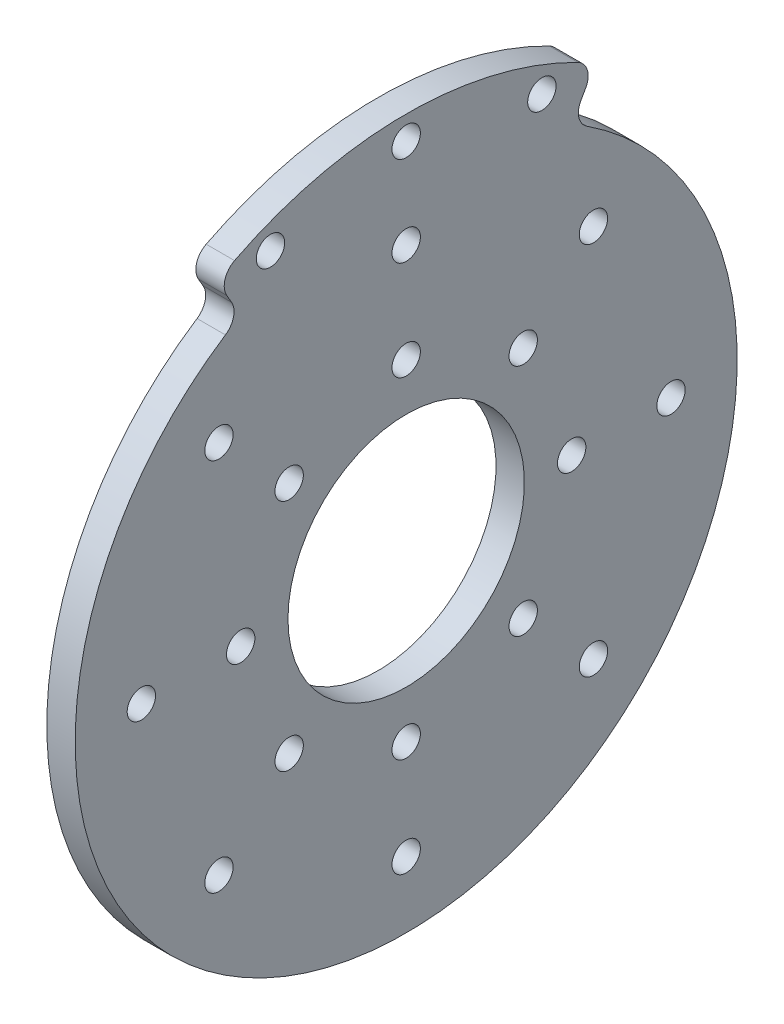
SolidWorks part; units mm, degrees
ref_plane "前视基准面" through (0, 0, 0) normal (0, 0, 1) x (1, 0, 0)
ref_plane "上视基准面" through (0, 0, 0) normal (0, 1, 0) x (1, 0, 0)
ref_plane "右视基准面" through (0, 0, 0) normal (1, 0, 0) x (0, 0, -1)
other "Configuration Table"
sketch "草图1" plane through (0, 0, 0) normal (1, 0, 0) x (0, 0, -1)
  circle A0 centre (0, 0) radius 35
  dimension "D1" = 70
extrude "凸台-拉伸1" add sketch "草图1" along normal blind 3
sketch "草图2" plane through (3, 0, 0) normal (1, 0, 0) x (0, 0, -1)
  circle A0 centre (0, 0) radius 26
  circle A1 centre (0, 0) radius 30
  circle A2 centre (0, 0) radius 28
  circle A3 centre (0, 28) radius 1.5
  circle A4 centre (19.799, 19.799) radius 1.5
  circle A5 centre (28, 0) radius 1.5
  circle A6 centre (19.799, -19.799) radius 1.5
  circle A7 centre (0, -28) radius 1.5
  circle A8 centre (-19.799, -19.799) radius 1.5
  circle A9 centre (-28, 0) radius 1.5
  circle A10 centre (-19.799, 19.799) radius 1.5
  point P24 (0, 0)
  dimension "D1" = 52
  dimension "D2" = 60
  dimension "D3" = 56
  dimension "D4" = 3
  dimension "D5" = 8
extrude "切除-拉伸1" cut sketch "草图2" against normal blind 3 contours A2 A10 | A2 A10 | A2 A6 | A2 A6 | A2 A7 | A2 A7 | A2 A8 | A2 A8 | A2 A9 | A2 A9 | A3 | A4 | A5
sketch "草图3" plane through (3, 0, 0) normal (1, 0, 0) x (0, 0, -1)
  circle A0 centre (0, 0) radius 15
  circle A1 centre (0, 0) radius 17.5
  circle A2 centre (0, 17.5) radius 1.5
  circle A3 centre (12.3744, 12.3744) radius 1.5
  circle A4 centre (17.5, 0) radius 1.5
  circle A5 centre (12.3744, -12.3744) radius 1.5
  circle A6 centre (0, -17.5) radius 1.5
  circle A7 centre (-12.3744, -12.3744) radius 1.5
  circle A8 centre (-17.5, 0) radius 1.5
  circle A9 centre (-12.3744, 12.3744) radius 1.5
  point P22 (0, 0)
  dimension "D1" = 30
  dimension "D2" = 35
  dimension "D3" = 3
  dimension "D4" = 8
extrude "切除-拉伸2" cut sketch "草图3" against normal blind 3 contours A9 | A2 | A3 | A4 | A5 | A6 | A7 | A8
sketch "草图4" plane through (0, 0, 0) normal (-1, 0, 0) x (0, 0, 1)
  circle A0 centre (0, 0) radius 12.5
  dimension "D1" = 25
extrude "切除-拉伸3" cut sketch "草图4" against normal blind 3
sketch "草图5" plane through (3, 0, 0) normal (1, 0, 0) x (0, 0, -1)
  line L0 (0, 0) -> (-20, 34.641)
  line L1 (0, 0) -> (20, 34.641)
  line L2 (-20, 34.641) -> (-17.5, 30.3109)
  line L3 (0, -1000) -> (0, 49000) construction
  line L4 (-20, 34.641) -> (-17.5, 30.3109)
  circle A0 centre (0, 0) radius 40
  circle A1 centre (0, 0) radius 40
  circle A2 centre (0, 0) radius 35 construction
  circle M21 centre (0, 0) radius 35
  dimension "D1" = 80
  dimension "D2" = 60
  dimension "D3" = 30
extrude "凸台-拉伸4" add sketch "草图5" against normal blind 3 contours L3 A1 L0 M21 | L3 L1 A0 M21
fillet "圆角1" radius 2 1 edges at (1.5, 34.641, 20)
fillet "圆角2" radius 2 1 edges at (1.5, 30.3109, 17.5)
fillet "圆角3" radius 2 1 edges at (1.5, 30.3109, -17.5)
fillet "圆角4" radius 2 1 edges at (1.5, 34.641, -20)
sketch "草图6" plane through (3, 0, 0) normal (1, 0, 0) x (0, 0, -1)
  line L0 (0, -1000) -> (0, 49000) construction
  circle A0 centre (0, 37.5) radius 1.5
  circle A1 centre (0, 0) radius 37.5
  circle A2 centre (14.3506, 34.6455) radius 1.5
  circle A3 centre (26.5165, 26.5165) radius 1.5
  circle A4 centre (34.6455, 14.3506) radius 1.5
  circle A5 centre (37.5, 0) radius 1.5
  circle A6 centre (34.6455, -14.3506) radius 1.5
  circle A7 centre (26.5165, -26.5165) radius 1.5
  circle A8 centre (14.3506, -34.6455) radius 1.5
  circle A9 centre (0, -37.5) radius 1.5
  circle A10 centre (-14.3506, -34.6455) radius 1.5
  circle A11 centre (-26.5165, -26.5165) radius 1.5
  circle A12 centre (-34.6455, -14.3506) radius 1.5
  circle A13 centre (-37.5, 0) radius 1.5
  circle A14 centre (-34.6455, 14.3506) radius 1.5
  circle A15 centre (-26.5165, 26.5165) radius 1.5
  circle A16 centre (-14.3506, 34.6455) radius 1.5
  point P41 (0, 0)
  dimension "D1" = 3
  dimension "D2" = 37.5
  dimension "D3" = 16
extrude "切除-拉伸4" cut sketch "草图6" against normal blind 3 contours A1 A16 | A1 A16 | A1 A2 | A1 A2 | A0 L0 A1 | L0 A0 A1 | L0 A1 A0 | A1 L0 A0
